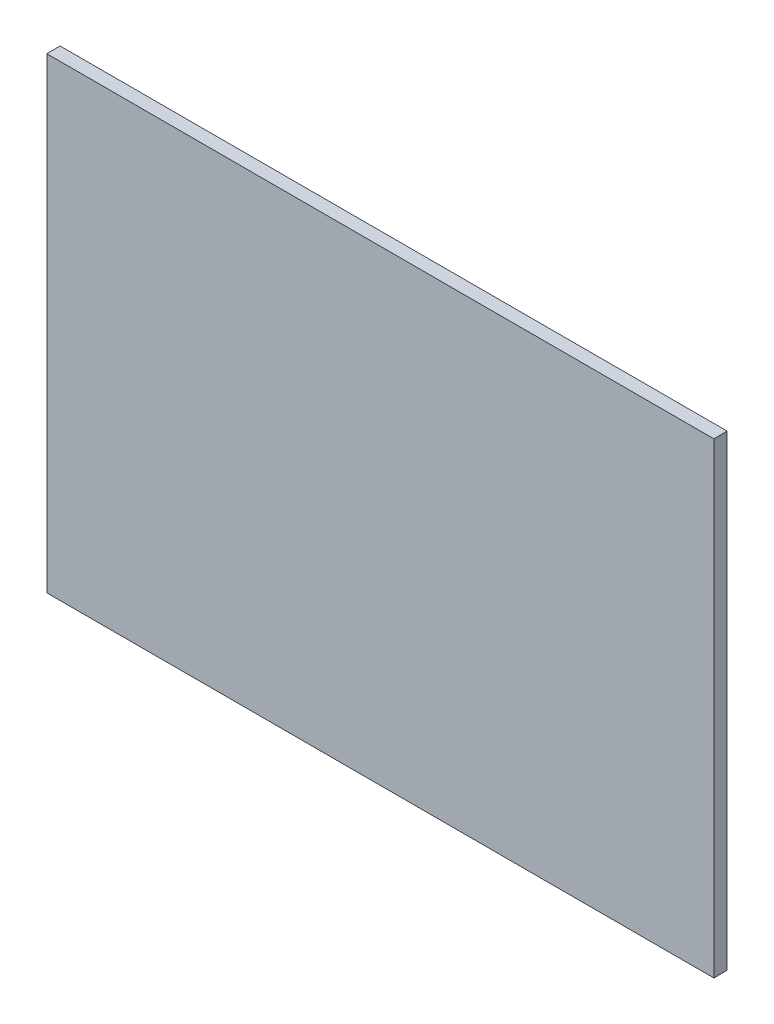
SolidWorks part; units mm, degrees
ref_plane "Front Plane" through (0, 0, 0) normal (0, 0, 1) x (1, 0, 0)
ref_plane "Top Plane" through (0, 0, 0) normal (0, 1, 0) x (1, 0, 0)
ref_plane "Right Plane" through (0, 0, 0) normal (1, 0, 0) x (0, 0, -1)
sketch "Sketch1" plane through (0, 0, 0) normal (0, 0, 1) x (1, 0, 0)
  line L1 (2500, -1750) -> (-2500, -1750)
  line L2 (2500, -1750) -> (2500, 1750)
  line L3 (2500, 1750) -> (-2500, 1750)
  line L4 (-2500, -1750) -> (-2500, 1750)
  line L5 (2500, -1750) -> (-2500, 1750) construction
  line L6 (2500, 1750) -> (-2500, -1750) construction
  point P0 (0, 0)
  dimension "D1" = 5000
  dimension "D2" = 3500
extrude "Boss-Extrude1" add sketch "Sketch1" along normal blind 100
